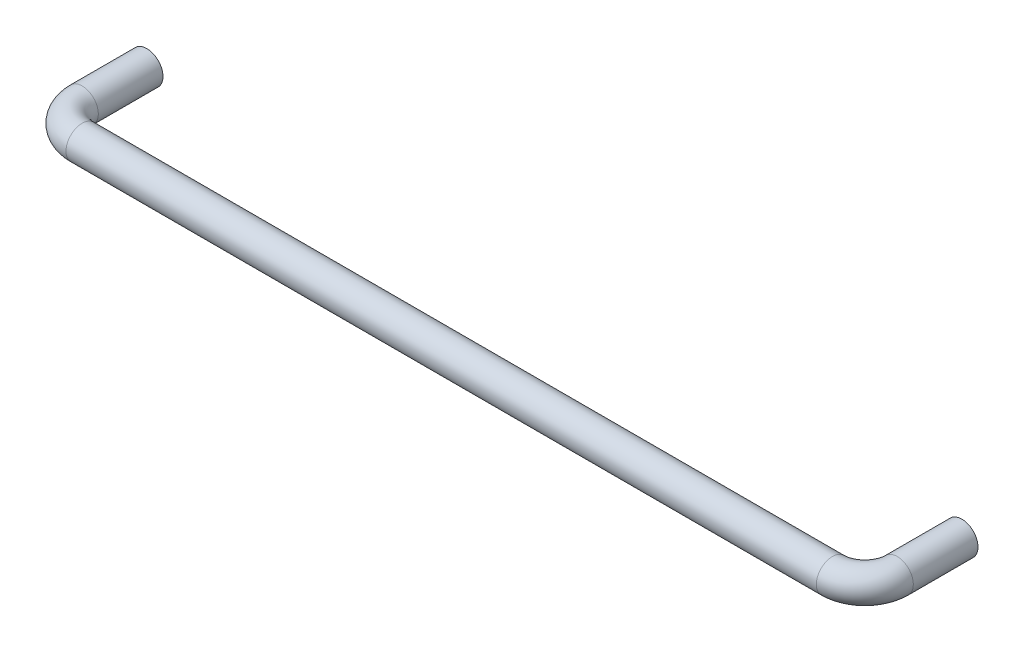
SolidWorks part; units mm, degrees
mirror "Mirror All1" of bodies 102
sweep "Base-Sweep" add profiles "Sketch1" path "3DSketch1"
sketch "Sketch1" plane through (0, 0, 0) normal (0, 0, 1) x (1, 0, 0)
  circle A0 centre (0, 0) radius 5
  dimension "D1" = 10
sketch3d "3DSketch1"
  line L0 (0, 0, 0) -> (0, 0, 20)
  line L1 (10, 0, 30) -> (126, 0, 30)
  line L2 (126, 0, 30) -> (126, 0, 0) construction
  line L3 (0, 0, 0) -> (126, 0, 0) construction
  arc A0 (0, 0, 20) -> (10, 0, 30) centre (10, 0, 20) ccw
  point P7 (0, 0, 30)
  point P8 (10, 10, 20)
  dimension "D1" = 10
  dimension "D2" = 30
  dimension "D3" = 126
hole_wizard "M3.0 (3.000000) Diameter Hole1" positions "Sketch3" profile "Sketch2" hole size "M3.0" standard "Ansi Metric"
sketch "Sketch3" plane through (0, 0, 0) normal (0, 0, -1) x (-1, 0, 0)
  point P0 (0, 0)
sketch "Sketch2" plane through (0, 0, 0) normal (1, 0, 0) x (0, 1, 0)
  line L0 (0, 0) -> (0, 3.9013)
  line L1 (0, 3.9013) -> (1.5, 3)
  line L2 (1.5, 3) -> (1.5, 0)
  line L5 (1.5, 0) -> (0, 0)
  line L10 (0, 3.9013) -> (-1.5, 3) construction
  line L11 (0, -6.35) -> (0, 107.95) construction
  dimension "Hole Dia." = 3
  dimension "Hole Depth" = 3
  dimension "Drill Angle" = 118
ref_plane "Front" through (0, 0, 0) normal (0, 0, 1) x (1, 0, 0)
ref_plane "Top" through (0, 0, 0) normal (0, 1, 0) x (1, 0, 0)
ref_plane "Right" through (0, 0, 0) normal (1, 0, 0) x (0, 0, -1)
